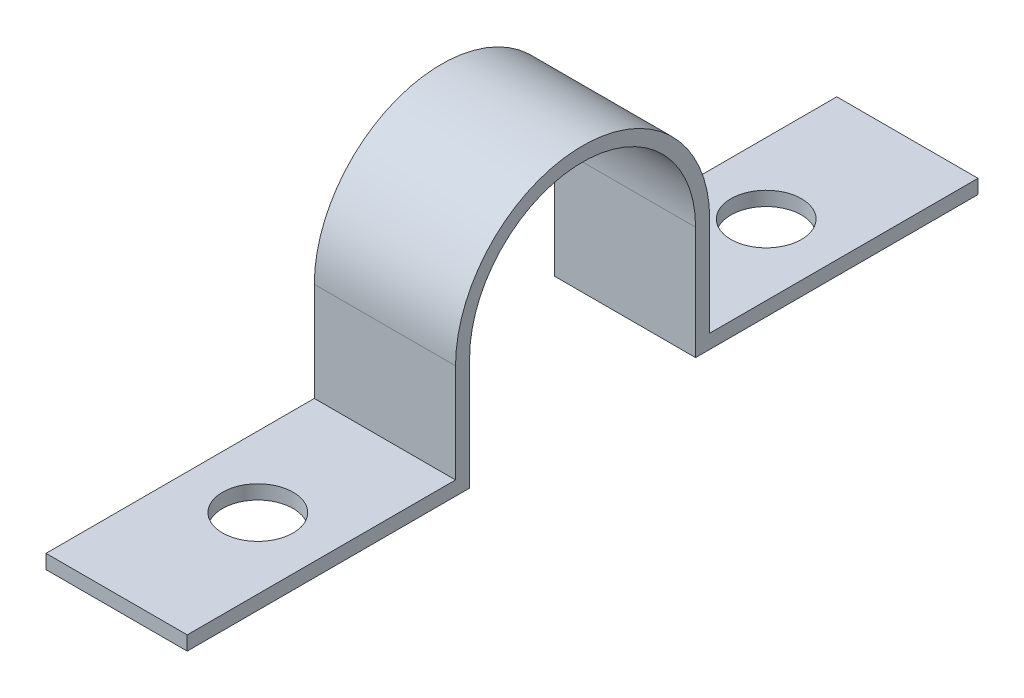
SolidWorks part; units mm, degrees
ref_plane "Piano frontale" through (0, 0, 0) normal (0, 0, 1) x (1, 0, 0)
ref_plane "Piano superiore" through (0, 0, 0) normal (0, 1, 0) x (1, 0, 0)
ref_plane "Piano destro" through (0, 0, 0) normal (1, 0, 0) x (0, 0, -1)
sketch "Schizzo2" plane through (0, 0, 0) normal (1, 0, 0) x (0, 0, -1)
  line L0 (-28, -7) -> (-9, -7)
  line L1 (-28, -8) -> (-8, -8)
  line L2 (8, 0) -> (8, -8)
  line L3 (-8, 0) -> (-8, -8)
  line L4 (8, -8) -> (28, -8)
  line L5 (-9, 0) -> (-9, -7)
  line L6 (9, 0) -> (9, -7)
  line L7 (9, -7) -> (28, -7)
  line L8 (-28, -7) -> (-28, -8)
  line L9 (28, -7) -> (28, -8)
  arc A0 (8, 0) -> (-8, 0) centre (0, 0) ccw
  arc A1 (9, 0) -> (-9, 0) centre (0, 0) ccw
  dimension "D3" = 1
extrude "Estrusione-Estrusione1" add sketch "Schizzo2" along normal blind 10
sketch "Schizzo3" plane through (0, -7, 0) normal (0, 1, 0) x (1, 0, 0)
  line L0 (5, 28) -> (5, 9) construction
  line L1 (10, 28) -> (0, 28) construction
  line L2 (10, 9) -> (0, 9) construction
  line L3 (0, 18) -> (10, 18) construction
  line L4 (0, 28) -> (0, 9) construction
  line L5 (10, 28) -> (10, 9) construction
  point P12 (5, 18)
hole_wizard "Fori filettati Ø5.0mm1" positions "Schizzo3D2" profile "Schizzo5" hole size "Ø5.0" standard "ISO"
sketch3d "Schizzo3D2"
  point P0 (5, -7, -18)
sketch "Schizzo5" plane through (5, -7, -18) normal (1, 0, 0) x (0, 0, 1)
  line L0 (0, 0) -> (0, 11.5022)
  line L1 (0, 11.5022) -> (2.5, 10)
  line L2 (2.5, 10) -> (2.5, 0)
  line L5 (2.5, 0) -> (0, 0)
  line L10 (0, 11.5022) -> (-2.5, 10) construction
  line L11 (0, -6.35) -> (0, 107.95) construction
  dimension "Hole Dia." = 5
  dimension "Hole Depth" = 10
  dimension "Drill Angle" = 118
sketch "Schizzo7" plane through (0, -7, 0) normal (0, 1, 0) x (1, 0, 0)
  line L0 (5, -28) -> (5, -9) construction
  line L1 (10, -28) -> (0, -28) construction
  line L2 (10, -9) -> (0, -9) construction
  line L3 (10, -18) -> (0, -18) construction
  line L4 (10, -9) -> (10, -28) construction
  line L5 (0, -9) -> (0, -28) construction
  point P12 (5, -18)
hole_wizard "Fori filettati Ø5.0mm2" positions "Schizzo3D3" profile "Schizzo8" hole size "Ø5.0" standard "ISO"
sketch3d "Schizzo3D3"
  point P0 (5, -7, 18)
sketch "Schizzo8" plane through (5, -7, 18) normal (1, 0, 0) x (0, 0, 1)
  line L0 (0, 0) -> (0, 11.5022)
  line L1 (0, 11.5022) -> (2.5, 10)
  line L2 (2.5, 10) -> (2.5, 0)
  line L5 (2.5, 0) -> (0, 0)
  line L10 (0, 11.5022) -> (-2.5, 10) construction
  line L11 (0, -6.35) -> (0, 107.95) construction
  dimension "Hole Dia." = 5
  dimension "Hole Depth" = 10
  dimension "Drill Angle" = 118
